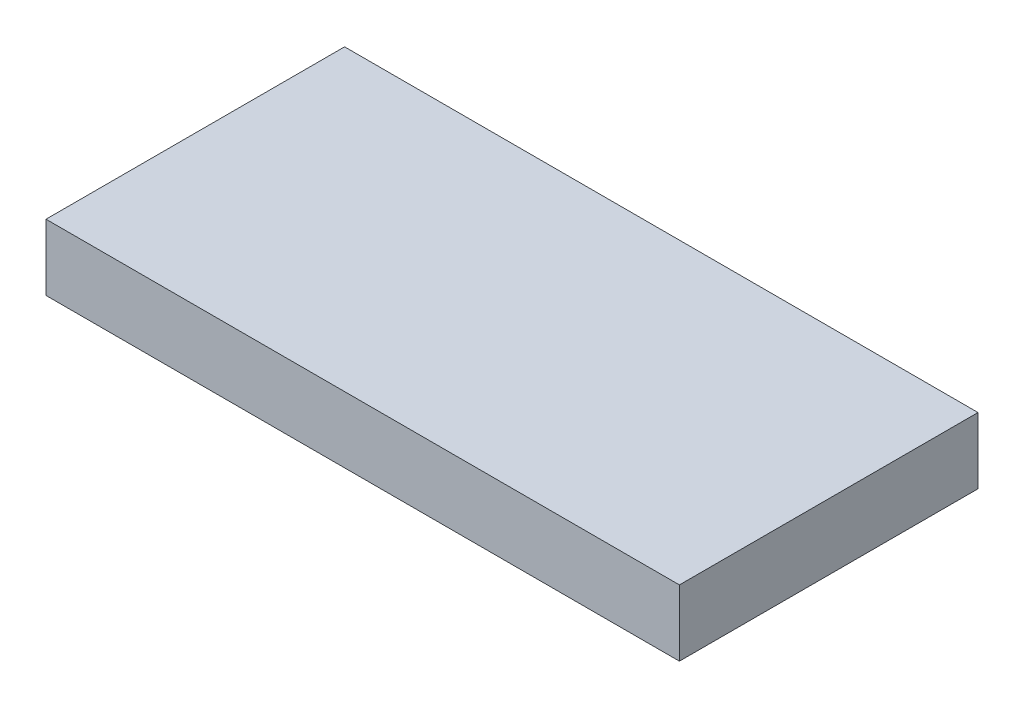
SolidWorks part; units mm, degrees
ref_plane "Front Plane" through (0, 0, 0) normal (0, 0, 1) x (1, 0, 0)
ref_plane "Top Plane" through (0, 0, 0) normal (0, 1, 0) x (1, 0, 0)
ref_plane "Right Plane" through (0, 0, 0) normal (1, 0, 0) x (0, 0, -1)
sketch "Sketch1" plane through (0, 0, 0) normal (0, 1, 0) x (1, 0, 0)
  line L1 (0, 0) -> (95.8787, 0)
  line L2 (0, 0) -> (0, -45.1965)
  line L3 (0, -45.1965) -> (95.8787, -45.1965)
  line L4 (95.8787, 0) -> (95.8787, -45.1965)
extrude "Boss-Extrude1" add sketch "Sketch1" along normal blind 10
